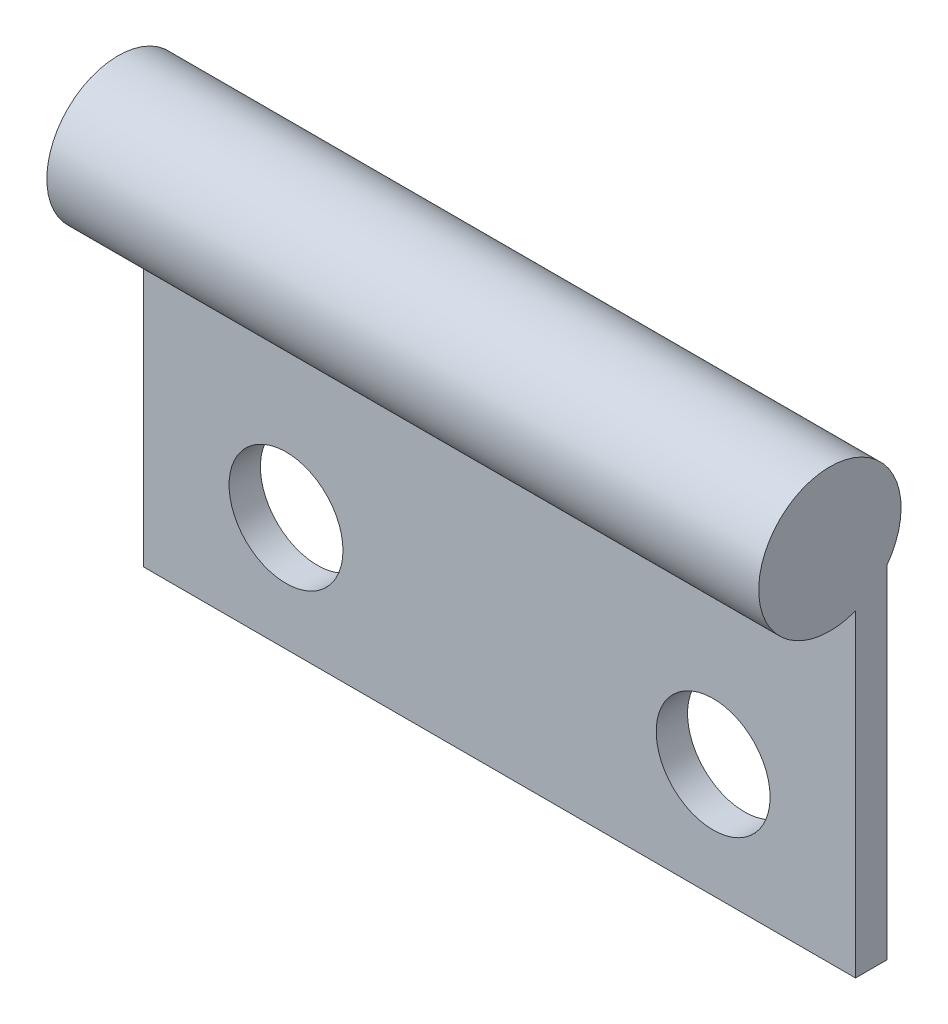
SolidWorks part; units mm, degrees
ref_plane "前视基准面" through (0, 0, 0) normal (0, 0, 1) x (1, 0, 0)
ref_plane "上视基准面" through (0, 0, 0) normal (0, 1, 0) x (1, 0, 0)
ref_plane "右视基准面" through (0, 0, 0) normal (1, 0, 0) x (0, 0, -1)
sketch "草图1" plane through (0, 0, 0) normal (0, 0, 1) x (1, 0, 0)
  line L0 (12.5, 0) -> (12.5, 4) construction
  line L1 (0, 0) -> (25, 0)
  line L2 (0, 0) -> (0, 13.5)
  line L3 (0, 13.5) -> (25, 13.5)
  line L4 (25, 0) -> (25, 13.5)
  line L5 (20, 4) -> (5, 4) construction
  circle A0 centre (5, 4) radius 2
  circle A1 centre (20, 4) radius 2
  point P10 (12.5, 4)
  dimension "D5" = 4
  dimension "D1" = 13.5
  dimension "D2" = 25
  dimension "D3" = 4
  dimension "D4" = 15
extrude "凸台-拉伸1" add sketch "草图1" along normal blind 1.1
sketch "草图2" plane through (0, 0, 0) normal (-1, 0, 0) x (0, 0, 1)
  line L1 (1.1, 13.5) -> (0, 13.5) construction
  line L2 (0, 13.5) -> (0, 0) construction
  circle A0 centre (2, 13.5) radius 2.5
  dimension "D1" = 5
  dimension "D2" = 2
extrude "凸台-拉伸2" add sketch "草图2" against normal up to surface (25 mm away) up to face at (25, 6.75, 0.55)
